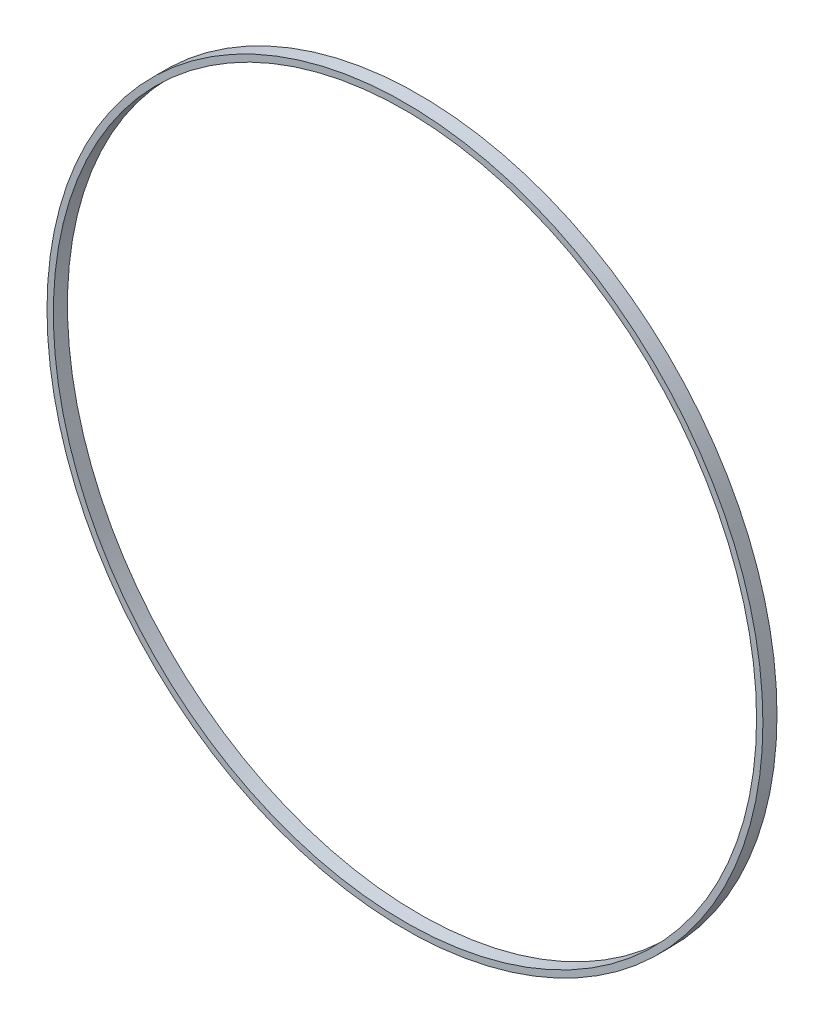
SolidWorks part; units mm, degrees
material "Caoutchouc"
ref_plane "Plan de face" through (0, 0, 0) normal (0, 0, 1) x (1, 0, 0)
ref_plane "Plan de dessus" through (0, 0, 0) normal (0, 1, 0) x (1, 0, 0)
ref_plane "Plan de droite" through (0, 0, 0) normal (1, 0, 0) x (0, 0, -1)
sketch "Esquisse1" plane through (0, 0, 0) normal (0, 0, 1) x (1, 0, 0)
  circle A0 centre (0, 0) radius 19.95
  circle A1 centre (0, 0) radius 20.31
  dimension "D1" = 39.9
  dimension "D2" = 0.36
extrude "Boss.-Extru.1" add sketch "Esquisse1" along normal blind 0.8
